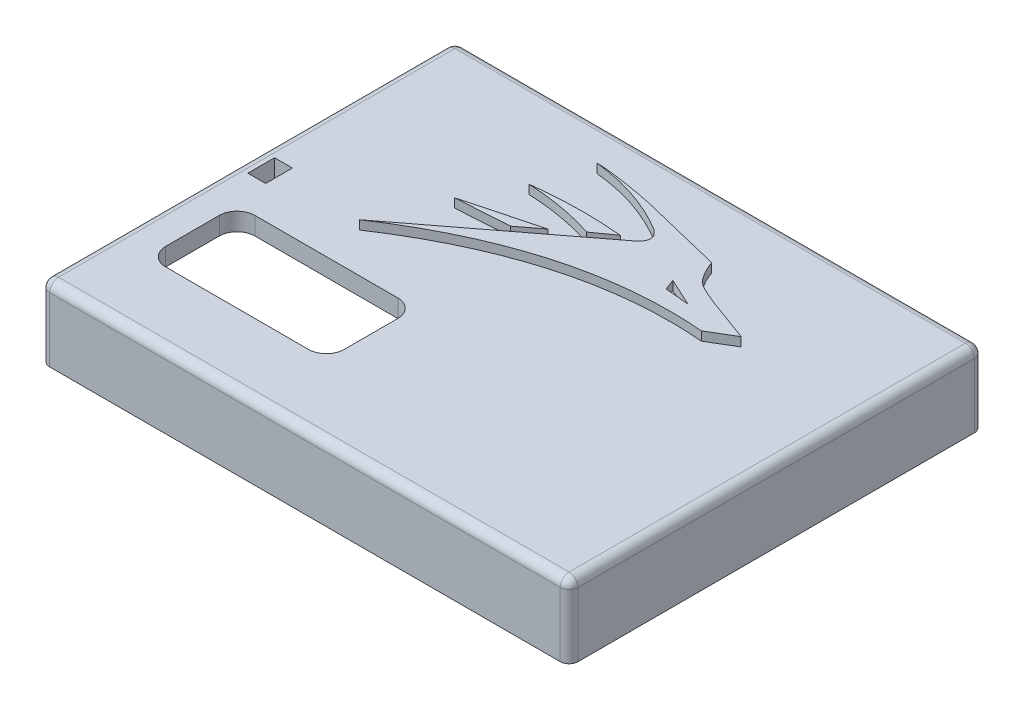
SolidWorks part; units mm, degrees
ref_plane "前视基准面" through (0, 0, 0) normal (0, 0, 1) x (1, 0, 0)
ref_plane "上视基准面" through (0, 0, 0) normal (0, 1, 0) x (1, 0, 0)
ref_plane "右视基准面" through (0, 0, 0) normal (1, 0, 0) x (0, 0, -1)
sketch "草图1" plane through (0, 0, 0) normal (1, 0, 0) x (0, 0, -1)
  line L0 (-3.2, 0) -> (-0.2, 0)
  line L1 (0, 0) -> (40, 0) construction
  line L2 (0, 0) -> (0, 6) construction
  line L3 (0, 6) -> (40, 6) construction
  line L4 (40, 0) -> (40, 6) construction
  line L5 (-3.2, 0) -> (-3.2, 8.2)
  line L6 (-3.2, 8.2) -> (43.2, 8.2)
  line L7 (43.2, 8.2) -> (43.2, 0)
  line L8 (43.2, 0) -> (40.2, 0)
  line L9 (-0.2, 0) -> (-0.2, 6.2)
  line L10 (-0.2, 6.2) -> (40.2, 6.2)
  line L11 (40.2, 0) -> (40.2, 6.2)
  dimension "D1" = 40
  dimension "D2" = 6
  dimension "D4" = 2
  dimension "D5" = 3
  dimension "D6" = 3
  dimension "D3" = 0.2
extrude "凸台-拉伸1" add sketch "草图1" along normal blind 57.2
sketch "草图2" plane through (0, 0, 0) normal (-1, 0, 0) x (0, 0, 1)
  line L0 (-20, 8.2) -> (-20, 0.5161) construction
  line L1 (-43.2, 8.2) -> (3.2, 8.2) construction
  line L2 (-40.2, 6.2) -> (-40.2, 0) construction
  line L3 (-40.2, 3.8) -> (-38.2, 3.8)
  line L4 (-40.2, 3.8) -> (-40.2, 2.2)
  line L5 (-40.2, 2.2) -> (-38.2, 2.2)
  line L6 (-38.2, 3.8) -> (-38.2, 2.2)
  line L7 (-40.2, 0) -> (-43.2, 0) construction
  line L8 (0.2, 2.2) -> (-1.8, 2.2)
  line L9 (-1.8, 3.8) -> (-1.8, 2.2)
  line L10 (0.2, 3.8) -> (-1.8, 3.8)
  line L11 (0.2, 3.8) -> (0.2, 2.2)
  dimension "D1" = 2.2
  dimension "D2" = 3.8
  dimension "D3" = 2
extrude "凸台-拉伸2" add sketch "草图2" against normal up to surface (57.2 mm away) up to face at (57.2, 3.6, -20)
chamfer "倒角1" distance 0.5 angle 45 6 edges at (0, 2.2, -0.8) (0, 3.8, -0.8) (0, 3, -1.8) (0, 2.2, -39.2) (0, 3, -38.2) (0, 3.8, -39.2)
sketch "草图3" plane through (57.2, 0, 0) normal (1, 0, 0) x (0, 0, -1)
  line L1 (-3.2, 8.2) -> (43.2, 8.2)
  line L2 (-3.2, 8.2) -> (-3.2, 0)
  line L3 (-3.2, 0) -> (43.2, 0)
  line L4 (43.2, 8.2) -> (43.2, 0)
extrude "凸台-拉伸3" add sketch "草图3" along normal blind 2
sketch "草图4" plane through (0, 8.2, 0) normal (0, 1, 0) x (1, 0, 0)
  line L0 (59.2, -3.2) -> (0, -3.2) construction
  line L1 (4, 14.8) -> (24, 14.8)
  line L2 (4, 14.8) -> (4, 4.8)
  line L3 (4, 4.8) -> (24, 4.8)
  line L4 (24, 14.8) -> (24, 4.8)
  line L5 (0, 43.2) -> (0, -3.2) construction
  dimension "D1" = 20
  dimension "D2" = 10
  dimension "D3" = 8
  dimension "D4" = 4
extrude "切除-拉伸1" cut sketch "草图4" against normal blind 2
fillet "圆角1" radius 1 8 edges at (59.2, 4.1, 3.2) (59.2, 4.1, -43.2) (0, 4.1, -43.2) (0, 4.1, 3.2) (0, 8.2, -20) (59.2, 8.2, -20) (29.6, 8.2, 3.2) (29.6, 8.2, -43.2)
fillet "圆角2" radius 2 4 edges at (4, 7.2, -4.8) (4, 7.2, -14.8) (24, 7.2, -4.8) (24, 7.2, -14.8)
sketch "草图5" plane through (0, 8.2, 0) normal (0, 1, 0) x (1, 0, 0)
  line L0 (1, 42.2) -> (1, -2.2) construction
  line L1 (3.5, 21.5) -> (1.5, 21.5)
  line L2 (3.5, 21.5) -> (3.5, 18.5)
  line L3 (3.5, 18.5) -> (1.5, 18.5)
  line L4 (1.5, 21.5) -> (1.5, 18.5)
  line L5 (0, -2.2) -> (0, 42.2) construction
  point P6 (1, 20)
  point P7 (1.5, 20)
  dimension "D1" = 3
  dimension "D2" = 2
  dimension "D3" = 1.5
extrude "切除-拉伸2" cut sketch "草图5" against normal blind 2
sketch "草图6" plane through (0, 8.2, 0) normal (0, 1, 0) x (1, 0, 0)
  line L0 (43.2102, 27.6092) -> (46.0046, 29.2782)
  line L1 (46.0046, 29.2782) -> (41.1537, 31.0523)
  line L2 (204.075, 349.6674) -> (967.4083, 349.6674) construction
  line L3 (29.3925, 32.3368) -> (27.1937, 30.7738)
  line L4 (30.6814, 32.541) -> (13.2735, 19.243)
  line L5 (16.4648, 26.6942) -> (24.73, 28.893)
  line L6 (24.73, 28.893) -> (22.3594, 27.082)
  line L7 (22.3594, 27.082) -> (16.4648, 26.6942)
  line L8 (36.7098, 30.9124) -> (37.1783, 29.6993)
  line L9 (37.1783, 29.6993) -> (39.8567, 29.4542)
  line L10 (39.8567, 29.4542) -> (36.7098, 30.9124)
  spline S0 degree 2 poles (13.2735, 19.243) (27.8286, 28.924) (43.2102, 27.6092) knots 0 0 0 0.904008 0.904008 0.904008
  spline S1 degree 3 poles (41.1537, 31.0523) (38.9176, 31.9368) (38.0815, 32.7836) (37.4296, 34.0398) (37.1783, 34.7999) knots 0 0 0 0 0.258598 0.606504 0.606504 0.606504 0.606504
  spline S2 degree 3 poles (37.1783, 34.7999) (27.4956, 37.1275) (28.5408, 37.0342) (22.2735, 38.0647) (21.1012, 38.0347) knots 0 0 0 0 0.625762 1 1 1 1
  spline S3 degree 2 poles (21.1012, 38.0347) (26.2756, 37.4919) (30.6859, 34.7999) knots 0 0 0 1 1 1
  spline S4 degree 2 poles (30.6859, 34.7999) (32.1765, 33.7223) (30.6814, 32.541) knots 0 0 0 1 1 1
  spline S5 degree 2 poles (19.2994, 32.1779) (24.3395, 32.8158) (29.3925, 32.3368) knots 0 0 0 1 1 1
  spline S6 degree 2 poles (19.2994, 32.1779) (23.3467, 32.0241) (27.1937, 30.7738) knots 0 0 0 1 1 1
  point P10 (36.7098, 30.9124)
extrude "凸台-拉伸4" add sketch "草图6" along normal blind 1
